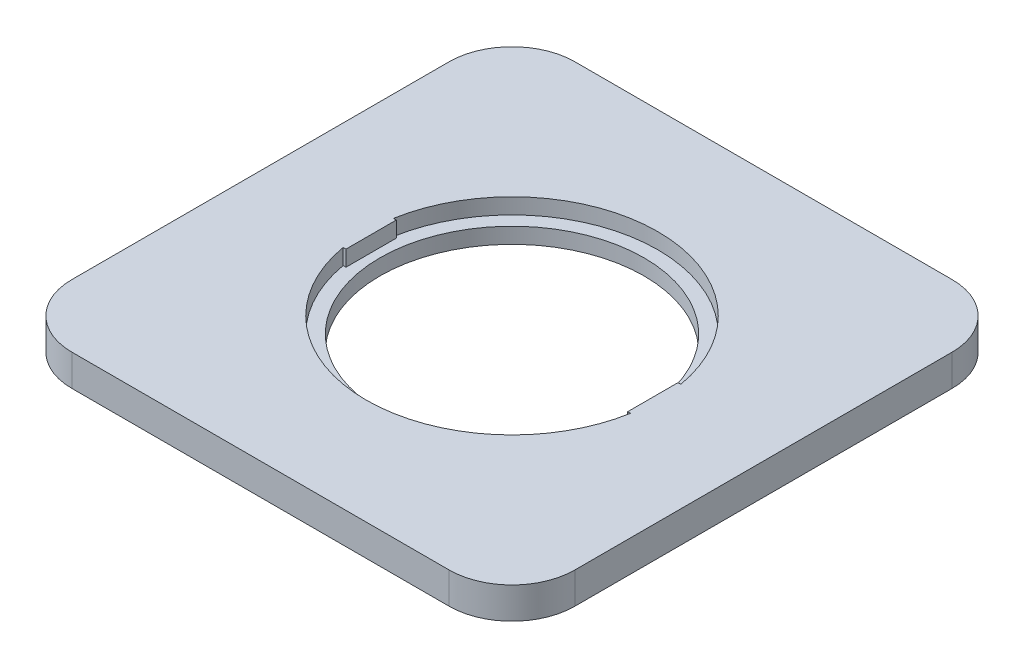
SolidWorks part; units mm, degrees
ref_plane "前视基准面" through (0, 0, 0) normal (0, 0, 1) x (1, 0, 0)
ref_plane "上视基准面" through (0, 0, 0) normal (0, 1, 0) x (1, 0, 0)
ref_plane "右视基准面" through (0, 0, 0) normal (1, 0, 0) x (0, 0, -1)
other "Configuration Table"
sketch "Sketch1" plane through (0, 0, 0) normal (0, 1, 0) x (1, 0, 0)
  line L1 (-30, -40) -> (30, -40)
  line L2 (-40, -30) -> (-40, 30)
  line L3 (-30, 40) -> (30, 40)
  line L4 (40, -30) -> (40, 30)
  line L5 (-40, -40) -> (40, 40) construction
  line L6 (-40, 40) -> (40, -40) construction
  arc A0 (30, -40) -> (40, -30) centre (30, -30) ccw
  arc A1 (-30, -40) -> (-40, -30) centre (-30, -30) cw
  arc A2 (-40, 30) -> (-30, 40) centre (-30, 30) cw
  arc A3 (30, 40) -> (40, 30) centre (30, 30) cw
  point P0 (0, 0)
  dimension "D3" = 10
  dimension "D1" = 80
  dimension "D2" = 80
extrude "Boss-Extrude1" add sketch "Sketch1" along normal blind 5
sketch "Sketch2" plane through (0, 5, 0) normal (0, 1, 0) x (1, 0, 0)
  circle A0 centre (0, 0) radius 21
  dimension "D1" = 42
extrude "Cut-Extrude1" cut sketch "Sketch2" against normal blind 8
sketch "Sketch3" plane through (0, 5, 0) normal (0, 1, 0) x (1, 0, 0)
  circle A0 centre (0, 0) radius 23.2
  dimension "D1" = 46.4
extrude "Cut-Extrude2" cut sketch "Sketch3" against normal blind 2.5
sketch "Sketch4" plane through (0, 2.5, 0) normal (0, 1, 0) x (1, 0, 0)
  line L0 (0, 0) -> (23.2, 0)
  line L1 (23.2, 0) -> (23.2, 4)
  line L2 (23.2, 4) -> (22.4, 4)
  line L3 (22.4, 4) -> (22.4, -4)
  line L4 (22.4, -4) -> (23.2, -4)
  line L5 (23.2, -4) -> (23.2, 0)
  line L6 (-23.2, 0) -> (-23.2, -4)
  line L7 (-23.2, -4) -> (-22.4, -4)
  line L8 (-22.4, -4) -> (-22.4, 4)
  line L9 (-22.4, 4) -> (-23.2, 4)
  line L10 (-23.2, 4) -> (-23.2, 0)
  circle A0 centre (0, 0) radius 23.2 construction
  point P18 (0, 0)
  circle M4 centre (0, 0) radius 23.2
  dimension "D1" = 8
  dimension "D2" = 4
  dimension "D3" = 0.8
  dimension "D4" = 2
extrude "Boss-Extrude2" add sketch "Sketch4" along normal up to surface (2.5 mm away) contours L8 L9 L7 M4 | L1 L2 L3 L4 L5 up to face at (0, 5, 23.2)
